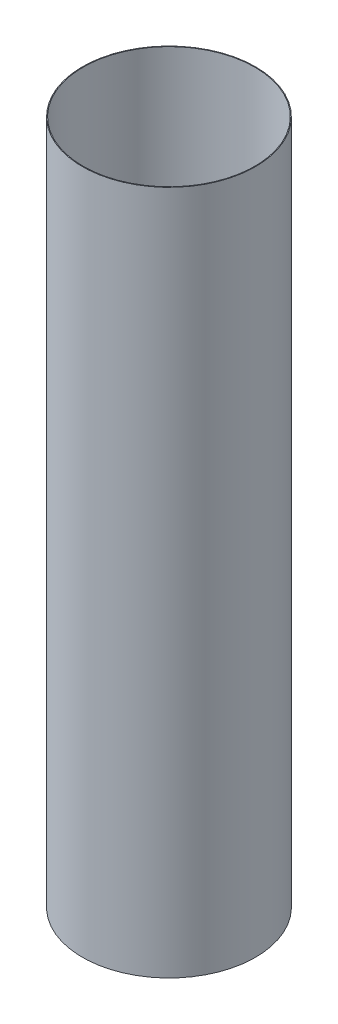
SolidWorks part; units mm, degrees
ref_plane "Plano frontal" through (0, 0, 0) normal (0, 0, 1) x (1, 0, 0)
ref_plane "Plano superior" through (0, 0, 0) normal (0, 1, 0) x (1, 0, 0)
ref_plane "Plano direito" through (0, 0, 0) normal (1, 0, 0) x (0, 0, -1)
sketch "Sketch1" plane through (0, 0, 0) normal (0, 0, 1) x (1, 0, 0)
  line L0 (0, 0) -> (11, 0)
  line L1 (11, 0) -> (11, 87)
  line L2 (11, 87) -> (0, 87)
  line L3 (0, 87) -> (0, 0)
  dimension "D1" = 11
  dimension "D2" = 87
revolve "Revolve4" add sketch "Sketch1" angle 360 about L1
sketch "Esboço1" plane through (0, 87, 0) normal (0, 1, 0) x (1, 0, 0)
  circle A0 centre (11, 0) radius 10.91
extrude "Corte-extrusão1" cut sketch "Esboço1" against normal blind 87
